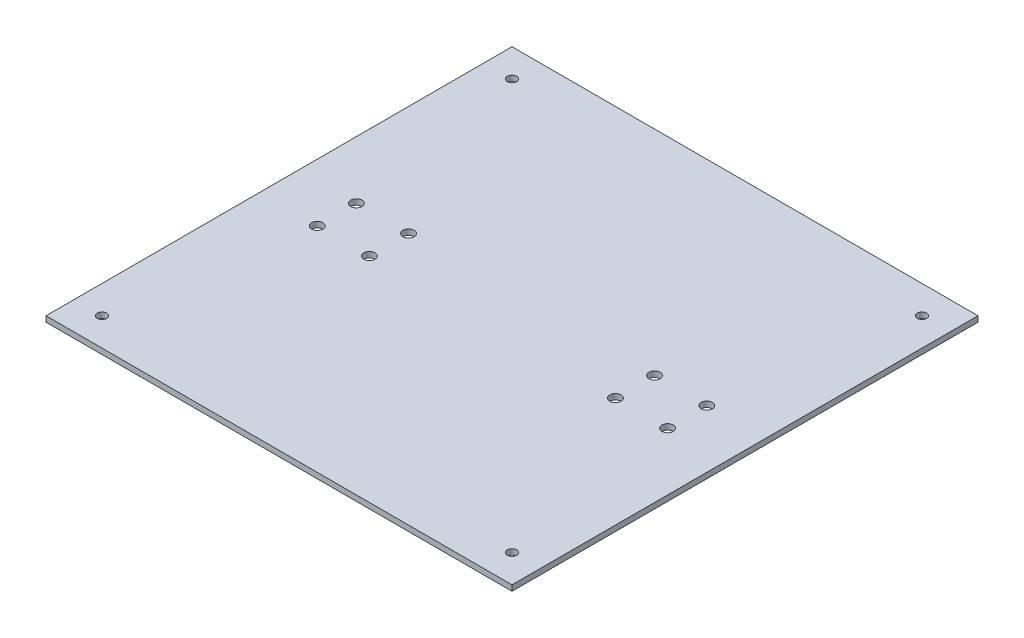
SolidWorks part; units mm, degrees
ref_plane "Front Plane" through (0, 0, 0) normal (0, 0, 1) x (1, 0, 0)
ref_plane "Top Plane" through (0, 0, 0) normal (0, 1, 0) x (1, 0, 0)
ref_plane "Right Plane" through (0, 0, 0) normal (1, 0, 0) x (0, 0, -1)
sketch "Sketch1" plane through (0, 0, 0) normal (0, 1, 0) x (1, 0, 0)
  line L1 (0, 0) -> (250, 0)
  line L2 (0, 0) -> (0, 250)
  line L3 (0, 250) -> (250, 250)
  line L4 (250, 0) -> (250, 250)
  dimension "D1" = 250
extrude "Boss-Extrude1" add sketch "Sketch1" along normal blind 3
sketch "Sketch2" plane through (0, 3, 0) normal (0, 1, 0) x (1, 0, 0)
  line L0 (0, 250) -> (250, 0) construction
  line L1 (45, 125) -> (205, 125) construction
  line L2 (15, 235) -> (235, 235) construction
  line L3 (15, 235) -> (15, 15) construction
  line L4 (15, 15) -> (235, 15) construction
  line L5 (235, 235) -> (235, 15) construction
  line L6 (15, 235) -> (235, 15) construction
  line L7 (15, 15) -> (235, 235) construction
  line L9 (31, 114.5) -> (59, 114.5) construction
  line L10 (31, 114.5) -> (31, 135.5) construction
  line L11 (31, 135.5) -> (59, 135.5) construction
  line L12 (59, 114.5) -> (59, 135.5) construction
  line L13 (31, 114.5) -> (59, 135.5) construction
  line L14 (31, 135.5) -> (59, 114.5) construction
  line L15 (191, 114.5) -> (219, 114.5) construction
  line L16 (191, 114.5) -> (191, 135.5) construction
  line L17 (191, 135.5) -> (219, 135.5) construction
  line L18 (219, 114.5) -> (219, 135.5) construction
  line L19 (191, 114.5) -> (219, 135.5) construction
  line L20 (191, 135.5) -> (219, 114.5) construction
  circle A0 centre (15, 235) radius 2.5
  circle A1 centre (235, 235) radius 2.5
  circle A2 centre (235, 15) radius 2.5
  circle A3 centre (15, 15) radius 2.5
  circle A4 centre (31, 135.5) radius 3
  circle A5 centre (59, 135.5) radius 3
  circle A6 centre (59, 114.5) radius 3
  circle A7 centre (31, 114.5) radius 3
  circle A8 centre (191, 135.5) radius 3
  circle A9 centre (219, 135.5) radius 3
  circle A10 centre (219, 114.5) radius 3
  circle A11 centre (191, 114.5) radius 3
  point P4 (125, 125)
  point P15 (125, 125)
  dimension "D2" = 5
  dimension "D6" = 6
  dimension "D1" = 220
  dimension "D3" = 160
  dimension "D4" = 28
  dimension "D5" = 21
extrude "Cut-Extrude1" cut sketch "Sketch2" against normal through all
